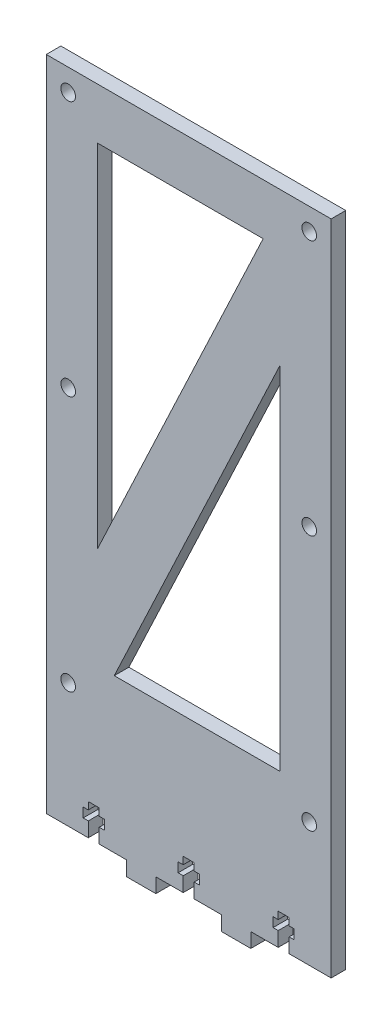
SolidWorks part; units mm, degrees
ref_plane "前视基准面" through (0, 0, 0) normal (0, 0, 1) x (1, 0, 0)
ref_plane "上视基准面" through (0, 0, 0) normal (0, 1, 0) x (1, 0, 0)
ref_plane "右视基准面" through (0, 0, 0) normal (1, 0, 0) x (0, 0, -1)
sketch "草图1" plane through (0, 0, 0) normal (0, 0, 1) x (1, 0, 0)
  line L7 (-43, 32.5) -> (35, 32.5)
  line L8 (-43, 32.5) -> (-43, -147.5)
  line L9 (-43, -147.5) -> (35, -147.5)
  line L10 (35, 32.5) -> (35, -147.5)
  dimension "D7" = 180
  dimension "D8" = 78
extrude "凸台-拉伸1" add sketch "草图1" along normal blind 4
sketch "草图2" plane through (0, 0, 4) normal (0, 0, 1) x (1, 0, 0)
  line L1 (35, 32.5) -> (-43, 32.5) construction
  line L42 (-15.7985, 32.5) -> (-15.7985, -147.5) construction
  line L43 (-43, -147.5) -> (35, -147.5) construction
  line L81 (9, -147.5) -> (9, -140.6052) construction
  line L82 (22, -147.5) -> (22, -155.1147) construction
  line L95 (-4, -147.5) -> (-4, -151.3851) construction
  line L96 (-31.5, -147.5) -> (-31.5, -143.5)
  line L97 (-31.5, -143.5) -> (-32.9, -143.5)
  line L98 (-32.9, -143.5) -> (-32.9, -140.9)
  line L99 (-32.9, -140.9) -> (-31.5, -140.9)
  line L100 (-31.5, -140.9) -> (-31.5, -138.9)
  line L101 (-28.5, -138.9) -> (-31.5, -138.9)
  line L102 (-28.5, -140.9) -> (-28.5, -138.9)
  line L103 (-27.1, -140.9) -> (-28.5, -140.9)
  line L104 (-27.1, -143.5) -> (-27.1, -140.9)
  line L105 (-28.5, -143.5) -> (-27.1, -143.5)
  line L106 (-28.5, -147.5) -> (-28.5, -143.5)
  line L107 (-31.5, -147.5) -> (-28.5, -147.5)
  line L108 (23.5, -147.5) -> (20.5, -147.5)
  line L109 (20.5, -147.5) -> (20.5, -143.5)
  line L110 (20.5, -143.5) -> (19.1, -143.5)
  line L111 (19.1, -143.5) -> (19.1, -140.9)
  line L112 (19.1, -140.9) -> (20.5, -140.9)
  line L113 (20.5, -140.9) -> (20.5, -138.9)
  line L114 (20.5, -138.9) -> (23.5, -138.9)
  line L115 (23.5, -140.9) -> (23.5, -138.9)
  line L116 (24.9, -140.9) -> (23.5, -140.9)
  line L117 (24.9, -143.5) -> (24.9, -140.9)
  line L118 (23.5, -143.5) -> (24.9, -143.5)
  line L119 (23.5, -147.5) -> (23.5, -143.5)
  line L120 (-5.5, -147.5) -> (-5.5, -143.5)
  line L121 (-5.5, -143.5) -> (-6.9, -143.5)
  line L122 (-6.9, -143.5) -> (-6.9, -140.9)
  line L123 (-6.9, -140.9) -> (-5.5, -140.9)
  line L124 (-5.5, -140.9) -> (-5.5, -138.9)
  line L125 (-2.5, -138.9) -> (-5.5, -138.9)
  line L126 (-2.5, -140.9) -> (-2.5, -138.9)
  line L127 (-1.1, -140.9) -> (-2.5, -140.9)
  line L128 (-1.1, -143.5) -> (-1.1, -140.9)
  line L129 (-2.5, -143.5) -> (-1.1, -143.5)
  line L130 (-2.5, -147.5) -> (-2.5, -143.5)
  line L131 (-5.5, -147.5) -> (-2.5, -147.5)
  point P112 (-30, -138.9)
  point P113 (22, -138.9)
  point P114 (-4, -138.9)
extrude "切除-拉伸1" cut sketch "草图2" against normal blind 4
sketch "草图4" plane through (0, -147.5, 0) normal (0, -1, 0) x (1, 0, 0)
  line L0 (-5.5, 2) -> (-2.5, 2)
  line L3 (-2.5, 4) -> (-4, 4)
  line L4 (-2.5, 2) -> (-2.2521, 2) construction
  line L5 (-2.5, 0) -> (-2.5, 4) construction
  circle A0 centre (-4, 2) radius 1.5
sketch "草图6" plane through (0, 0, 4) normal (0, 0, 1) x (1, 0, 0)
  line L0 (-17, -77.7) -> (-17, -134.4477) construction
  line L1 (-21.2, -77.7) -> (-12.8, -77.7) construction
  line L3 (-21, -143.5) -> (-13, -143.5)
  line L4 (-21, -143.5) -> (-21, -151.5)
  line L5 (-21, -151.5) -> (-13, -151.5)
  line L6 (-13, -143.5) -> (-13, -151.5)
  line L7 (-21, -143.5) -> (-13, -151.5) construction
  line L8 (-21, -151.5) -> (-13, -143.5) construction
  line L9 (5, -151.5) -> (13, -151.5)
  line L10 (5, -151.5) -> (5, -143.5)
  line L11 (5, -143.5) -> (13, -143.5)
  line L12 (13, -151.5) -> (13, -143.5)
  line L13 (5, -151.5) -> (13, -143.5) construction
  line L14 (5, -143.5) -> (13, -151.5) construction
  point P8 (9, -147.5)
  point P13 (-17, -147.5)
  dimension "D1" = 26
extrude "凸台-拉伸2" add sketch "草图6" against normal blind 4
sketch "草图7" plane through (0, 0, 0) normal (0, 0, -1) x (-1, 0, 0)
  line L0 (-35, 32.5) -> (43, 32.5) construction
  line L1 (-35, -147.5) -> (-35, 32.5) construction
  line L2 (-29, 26.5) -> (37, -113.5) construction
  line L3 (37, -113.5) -> (37, 26.5) construction
  line L4 (37, 26.5) -> (-29, 26.5) construction
  line L5 (29, 18.5) -> (-16.3842, 18.5)
  line L6 (-16.3842, 18.5) -> (29, -77.7694)
  line L7 (29, -77.7694) -> (29, 18.5)
  line L8 (37, -113.5) -> (-29, -113.5) construction
  line L9 (-29, -113.5) -> (-29, 26.5) construction
  line L10 (-21, -105.5) -> (-21, -9.2306)
  line L11 (-21, -9.2306) -> (24.3842, -105.5)
  line L12 (24.3842, -105.5) -> (-21, -105.5)
  circle A0 centre (-29, 26.5) radius 2
  circle A1 centre (-29, -43.5) radius 2
  circle A2 centre (-29, -113.5) radius 2
  circle A3 centre (37, -43.5) radius 2
  circle A4 centre (37, -113.5) radius 2
  circle A5 centre (37, 26.5) radius 2
  dimension "D1" = 6
  dimension "D2" = 6
  dimension "D5" = 8
  dimension "D6" = 8
  dimension "D3" = 3
  dimension "D4" = 2
extrude "切除-拉伸2" cut sketch "草图7" against normal blind 10
